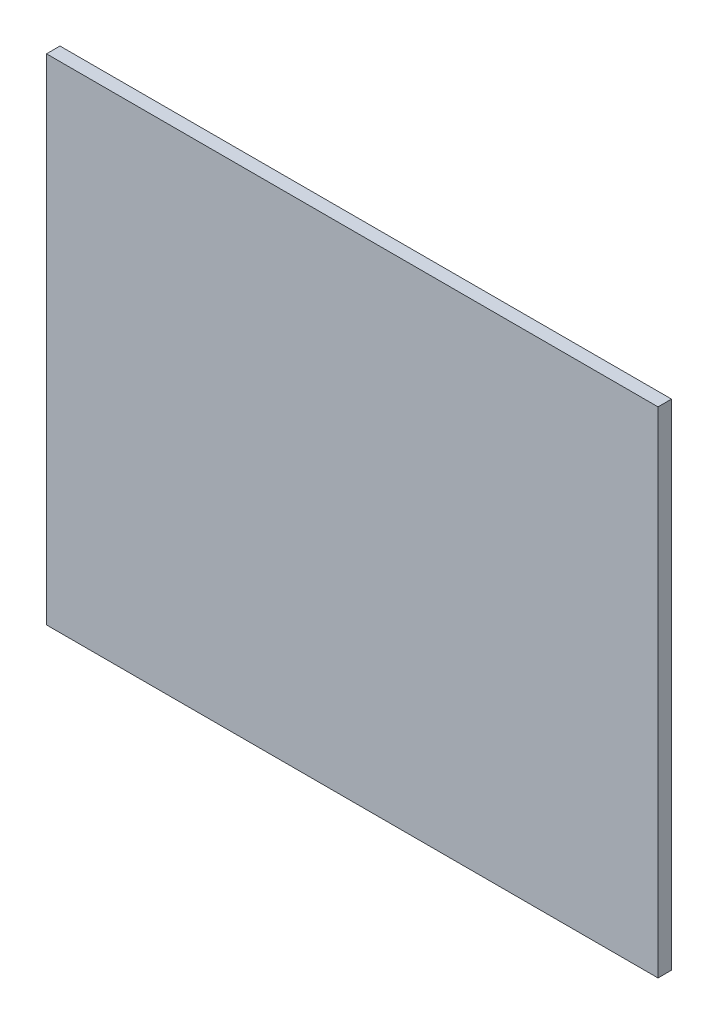
SolidWorks part; units mm, degrees
ref_plane "Front Plane" through (0, 0, 0) normal (0, 0, 1) x (1, 0, 0)
ref_plane "Top Plane" through (0, 0, 0) normal (0, 1, 0) x (1, 0, 0)
ref_plane "Right Plane" through (0, 0, 0) normal (1, 0, 0) x (0, 0, -1)
sketch "Sketch1" plane through (0, 0, 0) normal (0, 0, 1) x (1, 0, 0)
  line L1 (-68, 55) -> (68, 55)
  line L2 (-68, 55) -> (-68, -55)
  line L3 (-68, -55) -> (68, -55)
  line L4 (68, 55) -> (68, -55)
  line L5 (-68, 55) -> (68, -55) construction
  line L6 (-68, -55) -> (68, 55) construction
  point P0 (0, 0)
  dimension "D1" = 136
  dimension "D2" = 110
extrude "Boss-Extrude1" add sketch "Sketch1" along normal blind 3 contours L2 L3 L4 L1
